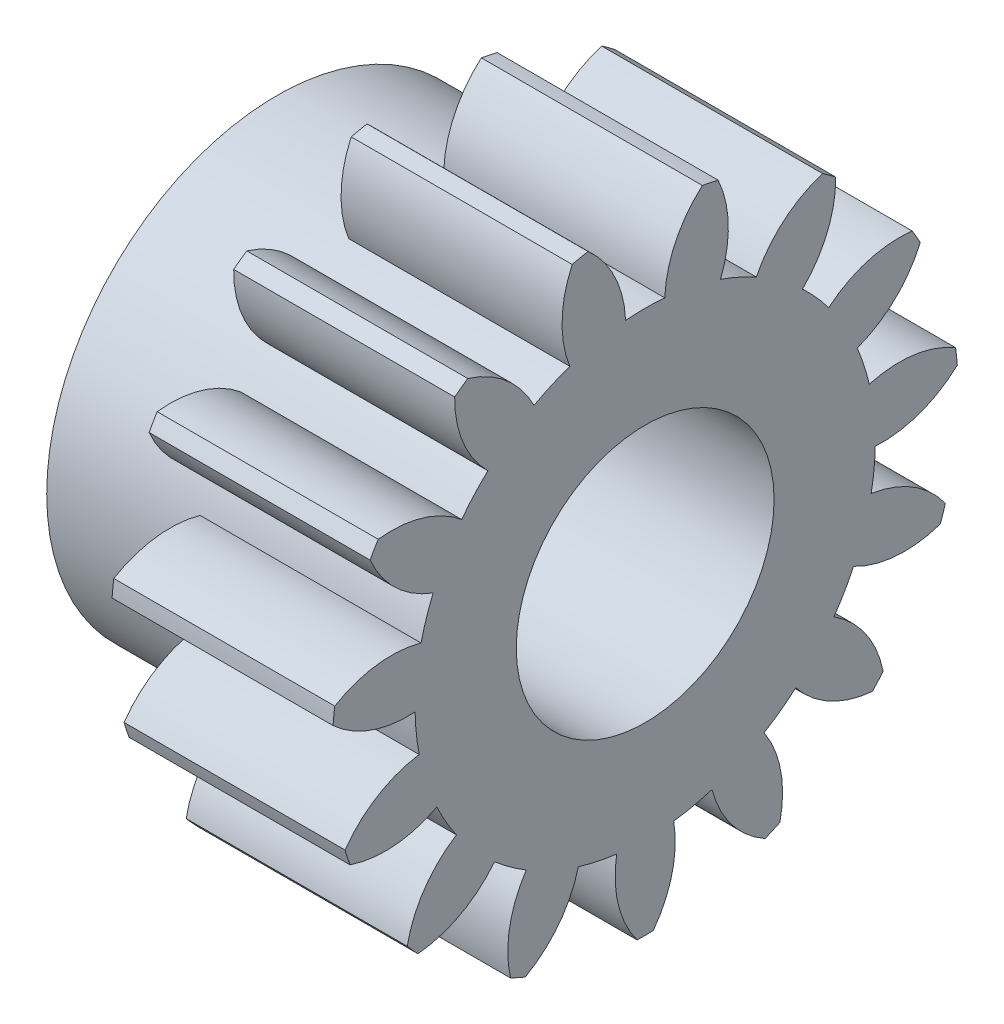
SolidWorks part; units mm, degrees
ref_plane "Plane1" through (0, 0, 0) normal (0, 0, 1) x (1, 0, 0)
ref_plane "Plane2" through (0, 0, 0) normal (0, 1, 0) x (1, 0, 0)
ref_plane "Plane3" through (0, 0, 0) normal (1, 0, 0) x (0, 0, -1)
sketch "HoldingSke" plane through (0, 0, 0) normal (0, 1, 0) x (1, 0, 0)
  line L0 (0, 0) -> (1.9319, -0.5176)
  line L1 (-15, 0) -> (100, 0) construction
  line L2 (0, 0) -> (-2.1039, 2.3779)
  line L3 (0, 0) -> (-11.863, 4.5341)
  line L4 (0, 0) -> (8.3417, 2.2352)
  line L5 (0, 0) -> (-4.6848, -1.7473)
  line L6 (0, 0) -> (-2.4869, -1.6779)
  line L7 (-2.1039, 2.3779) -> (-1.0276, 7.2607)
  line L8 (-76.2, 54.61) -> (-75.5, 54.61)
  line L9 (-71.009, 38.7566) -> (-53.1078, 45.2721)
  line L10 (-76.2, 71.12) -> (104.1128, 71.12)
  line L11 (0, 0) -> (-3, 0)
  line L12 (-76.2, 101.6) -> (-76.181, 101.6)
  line L13 (24.9733, 27.94) -> (52.9518, 28.4284)
  line L14 (24.9733, 27.94) -> (24.9743, 27.94)
  line L15 (24.9733, 27.94) -> (100.4006, 29.5858)
  line L16 (-63.627, -0.5) -> (-12.827, -0.5)
  circle A0 centre (0, 0) radius 2
  circle A1 centre (0, 0) radius 3.124
  circle A2 centre (0, 0) radius 5
  circle A3 centre (0, 0) radius 2
  dimension "MHD" = 6.248
  dimension "Hub_dia" = 10
  dimension "Bore" = 4
  dimension "MBD" = 4
  dimension "Num_teeth" = 15
  dimension "Pitch" = 2
  dimension "Overall_len" = 5
  dimension "Show_teeth" = 15
  dimension "Thickness" = 3
  dimension "OAL" = 5.0001
  dimension "T_dim" = 0.7
  dimension "Ap" = 20
  dimension "H" = 19.05
  dimension "Pitch_radius" = 180.3128
  dimension "Width" = 3
  dimension "Backlash" = 0.019
  dimension "Addendum_fac" = 1
  dimension "Dedendum_fac" = 1.25
  dimension "Clearance_fac" = 0.25
  dimension "Dedendum_add" = 0.001
  dimension "Module" = 0.5
sketch "BasProSke" plane through (0, 0, 0) normal (0, 1, 0) x (1, 0, 0)
  line L0 (-10, 0) -> (60, 0) construction
  line L1 (0, 0) -> (0, 4.25)
  line L2 (0, 0) -> (3, 0)
  line L3 (3, 0) -> (3, 4.25)
  line L4 (3, 4.25) -> (0, 4.25)
  dimension "Thickness" = 3
  dimension "Diameter" = 8.5
revolve "Base-Revolve" add sketch "BasProSke" angle 360 about L0
sketch "TooCutSke" plane through (0, 0, 0) normal (1, 0, 0) x (0, 0, -1)
  line L1 (0, 0) -> (0, 107) construction
  line L2 (0, 0) -> (-0.4252, 3.7258) construction
  line L3 (0, 0) -> (-1.5522, 7.3025) construction
  line L4 (-0.4252, 3.7258) -> (-0.7761, 3.6512) construction
  arc A0 (0.2658, 3.1127) -> (-0.2658, 3.1127) centre (0, 0) ccw
  arc A1 (0.8008, 4.1997) -> (-0.8008, 4.1997) centre (0, 0) ccw
  circle A2 centre (0, 0) radius 3.75 construction
  circle A3 centre (0, 0) radius 3.5238 construction
  arc A4 (-0.2658, 3.1127) -> (-0.8008, 4.1997) centre (-1.7645, 3.0503) ccw
  arc A5 (0.8008, 4.1997) -> (0.2658, 3.1127) centre (1.7645, 3.0503) ccw
  dimension "Root_dia" = 6.248
  dimension "Overcut_dia" = 8.5508
  dimension "Pitch_dia" = 7.5
  dimension "Base_dia" = 7.0477
  dimension "Flank_rad" = 1.5
  dimension "Half_ang" = 12
  dimension "Half_CT" = 0.3587
extrude "ToothCut" cut sketch "TooCutSke" along normal through all
fillet "Breaks" [suppressed] radius 0.01
fillet "RootFillets" [suppressed] radius 0.126
pattern_circular "TeethCuts" count 15 every 24 about axis through (-10, 0, 0) along (1, 0, 0) of "ToothCut", "RootFillets", "Breaks"
sketch "HubNeaOneSke" plane through (0, 0, 0) normal (-1, 0, 0) x (0, 0, 1)
  circle A0 centre (0, 0) radius 3.124
  dimension "Diameter" = 6.248
extrude "HubNearOne" add sketch "HubNeaOneSke" along normal blind 2.0001
sketch "HubNeaBotSke" plane through (0, 0, 0) normal (-1, 0, 0) x (0, 0, 1)
  circle A0 centre (0, 0) radius 3.124
  dimension "Diameter" = 6.248
extrude "HubNearBoth" [suppressed] add sketch "HubNeaBotSke" along normal blind 1
ref_plane "FarPln" through (3, 0, 0) normal (1, 0, 0) x (0, 0, -1)
sketch "HubFarSke" plane through (3, 0, 0) normal (1, 0, 0) x (0, 0, -1)
  circle A0 centre (0, 0) radius 3.124
  dimension "Diameter" = 6.248
extrude "HubFar" [suppressed] add sketch "HubFarSke" along normal blind 1
sketch "BorSke" plane through (0, 0, 0) normal (1, 0, 0) x (0, 0, -1)
  circle A0 centre (0, 0) radius 1.75
  dimension "D1" = 3.5
extrude "Bore" cut sketch "BorSke" along normal mid plane 10.0001
sketch "KeySke" plane through (0, 0, 0) normal (1, 0, 0) x (0, 0, -1)
  line L0 (-0.8, 0) -> (-0.8, 2.7)
  line L1 (-0.8, 2.7) -> (0.8, 2.7)
  line L2 (0.8, 2.7) -> (0.8, 0)
  line L3 (0, 0) -> (0, 34) construction
  line L4 (-0.8, 0) -> (0.8, 0)
  dimension "Offset" = 2.7
  dimension "Width" = 1.6
extrude "Keyway" [suppressed] cut sketch "KeySke" along normal mid plane 10.0001
pattern_circular "Keyway2" [suppressed] count 2 every 90 about axis through (-10, 0, 0) along (1, 0, 0)
equation "' \"Module@HoldingSke\" = 6.35"
equation "' \"Num_teeth@HoldingSke\" = 12"
equation "' \"Ap@HoldingSke\" =  20"
equation "' \"Ap@HoldingSke\" = 20"
equation "' \"Width@HoldingSke\" = 0.5 * 25.4"
equation "' \"Hub_dia@HoldingSke\"= 1 * 25.4"
equation "' \"Hub_dia@HoldingSke\" = 1 * 25.4"
equation "' \"Overall_len@HoldingSke\" = 1.0 * 25.4"
equation "' \"Bore@HoldingSke\" = 0.75 * 25.4"
equation "' \"T_dim@HoldingSke\" = 0.1 * 25.4"
equation "' \"Width@KeySke\" = 0.25 * 25.4"
equation "' \"Show_teeth@HoldingSke\" = 13"
equation "' \"Backlash@HoldingSke\" = 0.009 * 25.4"
equation "' \"Addendum_fac@HoldingSke\" = 1.0"
equation "' \"Dedendum_fac@HoldingSke\" = 1.25"
equation "' \"Dedendum_add@HoldingSke\" = 0.00005 * 25.4"
equation "' \"Clearance_fac@HoldingSke\" = 0.25"
equation "\"Pitch@HoldingSke\" = 1 / \"Module@HoldingSke\""
equation "\"Overcut_dia@TooCutSke\" = (\"Num_teeth@HoldingSke\" + 2 * \"Addendum_fac@HoldingSke\") / \"Pitch@HoldingSke\" + 0.002 * 25.4"
equation "\"Pitch_dia@TooCutSke\" = \"Num_teeth@HoldingSke\" / \"Pitch@HoldingSke\""
equation "\"Base_dia@TooCutSke\" = \"Num_teeth@HoldingSke\" / \"Pitch@HoldingSke\" * cos((\"Ap@HoldingSke\"  * 3.14159265 / 180))"
equation "\"Root_dia@TooCutSke\" = (\"Num_teeth@HoldingSke\" + 2) / \"Pitch@HoldingSke\" - 2 * (\"Addendum_fac@HoldingSke\" + \"Dedendum_fac@HoldingSke\") / \"Pitch@HoldingSke\" - \"Dedendum_add@HoldingSke\" * 2"
equation "\"Half_ang@TooCutSke\" = 180 / \"Num_teeth@HoldingSke\""
equation "\"Half_CT@TooCutSke\" = \"Num_teeth@HoldingSke\" / \"Pitch@HoldingSke\" * sin((3.14159265 / 2 / \"Num_teeth@HoldingSke\")) / 2 - 7 * \"Backlash@HoldingSke\" / 4"
equation "\"Flank_rad@TooCutSke\" = \"Num_teeth@HoldingSke\" / \"Pitch@HoldingSke\" / 5"
equation "\"Radius@RootFillets\" = \"Clearance_fac@HoldingSke\" / \"Pitch@HoldingSke\" + \"Dedendum_add@HoldingSke\""
equation "\"Break_rad@Breaks\" = 0.02 / \"Pitch@HoldingSke\""
equation "\"Thickness@HoldingSke\" = \"Width@HoldingSke\""
equation "\"OAL@HoldingSke\" = \"Thickness@HoldingSke\""
equation "\"MHD@HoldingSke\" = (\"Num_teeth@HoldingSke\" + 2) / \"Pitch@HoldingSke\" - 2 * (\"Addendum_fac@HoldingSke\" + \"Dedendum_fac@HoldingSke\")  / \"Pitch@HoldingSke\" - \"Dedendum_add@HoldingSke\" * 2"
equation "\"MBD@HoldingSke\" = (\"Num_teeth@HoldingSke\" + 2) / \"Pitch@HoldingSke\" - 2 * (\"Addendum_fac@HoldingSke\" + \"Dedendum_fac@HoldingSke\")  / \"Pitch@HoldingSke\" - \"Dedendum_add@HoldingSke\" * 2 - 0.002 * 25.4"
equation "\"MHD@HoldingSke\" = ((sgn( \"MHD@HoldingSke\" - \"Hub_dia@HoldingSke\" )-1)*( \"MHD@HoldingSke\" - \"Hub_dia@HoldingSke\" ))/-2+ \"Hub_dia@HoldingSke\""
equation "\"MBD@HoldingSke\" = ((sgn( \"MBD@HoldingSke\" - \"Bore@HoldingSke\" )-1)*( \"MBD@HoldingSke\" - \"Bore@HoldingSke\" ))/-2+ \"Bore@HoldingSke\""
equation "\"OAL@HoldingSke\" = ((sgn( \"OAL@HoldingSke\" - \"Overall_len@HoldingSke\" )+1)*( \"OAL@HoldingSke\" - \"Overall_len@HoldingSke\" ))/2 + \"Overall_len@HoldingSke\" + 0.000002 * 25.4"
equation "\"Num_teeth@TeethCuts\" = int( \"Show_teeth@HoldingSke\" ) + 1"
equation "\"Num_teeth@TeethCuts\" = ((sgn( \"Num_teeth@TeethCuts\" - \"Num_teeth@HoldingSke\" )-1)*( \"Num_teeth@TeethCuts\" - \"Num_teeth@HoldingSke\" ))/-2+ \"Num_teeth@HoldingSke\""
equation "\"Num_teeth@TeethCuts\" = ((sgn( \"Num_teeth@TeethCuts\" - 2.0)+1)*( \"Num_teeth@TeethCuts\" - 2.0))/2 +2.0"
equation "\"Angle@TeethCuts\" = 360.0 / \"Num_teeth@HoldingSke\""
equation "\"Diameter@BasProSke\" = (\"Num_teeth@HoldingSke\" + 2 * \"Addendum_fac@HoldingSke\") / \"Pitch@HoldingSke\""
equation "\"Thickness@BasProSke\"  = \"Thickness@HoldingSke\""
equation "' \"Fillet_rad@BasProSke\" =  \"Thickness@HoldingSke\" * 0.05"
equation "' \"Fillet_rad@BasProSke\" = \"Thickness@HoldingSke\" * 0.05"
equation "\"MHD@HoldingSke\" = ((sgn( \"MHD@HoldingSke\" - \"Root_dia@TooCutSke\" )-1)*( \"MHD@HoldingSke\" - \"Root_dia@TooCutSke\" ))/-2+ \"Root_dia@TooCutSke\""
equation "\"Diameter@HubNeaOneSke\" = \"MHD@HoldingSke\""
equation "\"Length@HubNearOne\" = \"OAL@HoldingSke\" - \"Thickness@BasProSke\""
equation "\"Diameter@HubNeaBotSke\" = \"MHD@HoldingSke\""
equation "\"Length@HubNearBoth\" = ( \"OAL@HoldingSke\" - \"Thickness@BasProSke\" ) / 2.0"
equation "\"Thickness@FarPln\" = \"Thickness@BasProSke\""
equation "\"Diameter@HubFarSke\" = \"MHD@HoldingSke\""
equation "\"Length@HubFar\" = ( \"OAL@HoldingSke\" - \"Thickness@BasProSke\" ) / 2.0"
equation "\"D1@Bore\" = \"OAL@HoldingSke\" * 2.0"
equation "\"D1@Keyway\" = \"OAL@HoldingSke\" * 2.0"
equation "\"Offset@KeySke\" = \"T_dim@HoldingSke\" + \"MBD@HoldingSke\" / 2.0"
